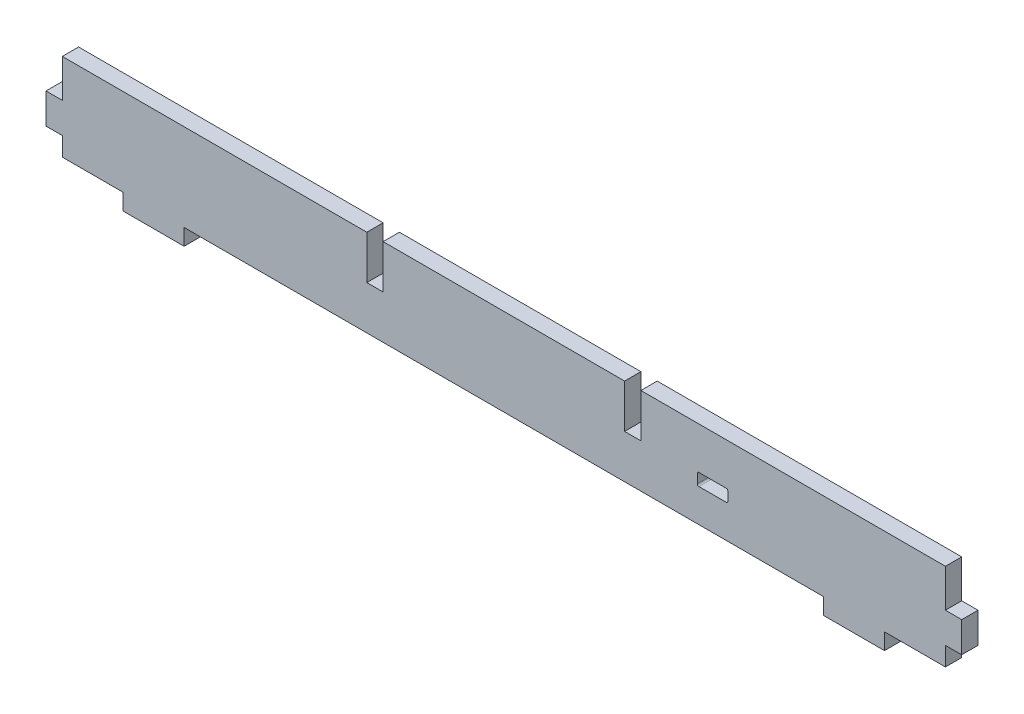
SolidWorks part; units mm, degrees
ref_plane "Front Plane" through (0, 0, 0) normal (0, 0, 1) x (1, 0, 0)
ref_plane "Top Plane" through (0, 0, 0) normal (0, 1, 0) x (1, 0, 0)
ref_plane "Right Plane" through (0, 0, 0) normal (1, 0, 0) x (0, 0, -1)
sketch "Model" plane through (0, 0, 0) normal (0, 0, 1) x (1, 0, 0)
  line L32 (0, 0) -> (0, 28.65) construction
  line L33 (-145, 0) -> (-125, 0)
  line L34 (-145, 0) -> (-145, 6.15)
  line L35 (-145, 28.65) -> (-45, 28.65)
  line L36 (145, 0) -> (145, 6.15)
  line L37 (-145, 16.15) -> (-145, 28.65)
  line L38 (105, 0) -> (105, -5.35)
  line L39 (-125, 0) -> (-125, -5.35)
  line L40 (-125, -5.35) -> (-105, -5.35)
  line L41 (-105, 0) -> (-105, -5.35)
  line L42 (-145, 6.15) -> (-150.35, 6.15)
  line L43 (-105, 0) -> (105, 0)
  line L44 (-145, 16.15) -> (-150.35, 16.15)
  line L45 (-150.35, 6.15) -> (-150.35, 16.15)
  line L46 (125, -5.35) -> (105, -5.35)
  line L47 (125, 0) -> (125, -5.35)
  line L48 (150.35, 6.15) -> (150.35, 16.15)
  line L49 (145, 16.15) -> (150.35, 16.15)
  line L50 (145, 6.15) -> (150.35, 6.15)
  line L51 (125, 0) -> (145, 0)
  line L52 (145, 16.15) -> (145, 28.65)
  line L53 (-39.65, 28.65) -> (39.65, 28.65)
  line L54 (45, 28.65) -> (45, 14.325)
  line L55 (-45, 28.65) -> (-45, 14.325)
  line L56 (-45, 14.325) -> (-39.65, 14.325)
  line L57 (-39.65, 28.65) -> (-39.65, 14.325)
  line L58 (45, 14.325) -> (39.65, 14.325)
  line L59 (39.65, 28.65) -> (39.65, 14.325)
  line L60 (45, 28.65) -> (145, 28.65)
  line L62 (64.04, 14.85) -> (73.04, 14.85)
  line L63 (63.54, 14.35) -> (63.54, 11.35)
  line L64 (64.04, 10.85) -> (73.04, 10.85)
  line L65 (73.54, 14.35) -> (73.54, 11.35)
  arc A4 (64.04, 14.85) -> (63.54, 14.35) centre (64.04, 14.35) ccw
  arc A5 (73.54, 14.35) -> (73.04, 14.85) centre (73.04, 14.35) ccw
  arc A6 (63.54, 11.35) -> (64.04, 10.85) centre (64.04, 11.35) ccw
  arc A7 (73.04, 10.85) -> (73.54, 11.35) centre (73.04, 11.35) ccw
  dimension "D26" = 1
  dimension "D2" = 5.35
  dimension "D4" = 20
  dimension "D7" = 20
  dimension "D8" = 10
  dimension "D9" = 5.35
  dimension "D12" = 6.15
  dimension "D13" = 290
  dimension "D14" = 28.65
  dimension "D18" = 5.35
  dimension "D19" = 14.325
  dimension "D22" = 100
  dimension "D27" = 10
  dimension "D28" = 4
  dimension "D30" = 71.46
  dimension "D32" = 10.85
extrude "Boss-Extrude1" add sketch "Model" along normal blind 5.35
equation "\"mdfthick\"=5.35"
equation "\"D2@Model\"=\"mdfthick\""
equation "\"D9@Model\"=\"mdfthick\""
equation "\"D18@Model\"=\"mdfthick\""
equation "\"D1@Boss-Extrude1\"=\"mdfthick\""
